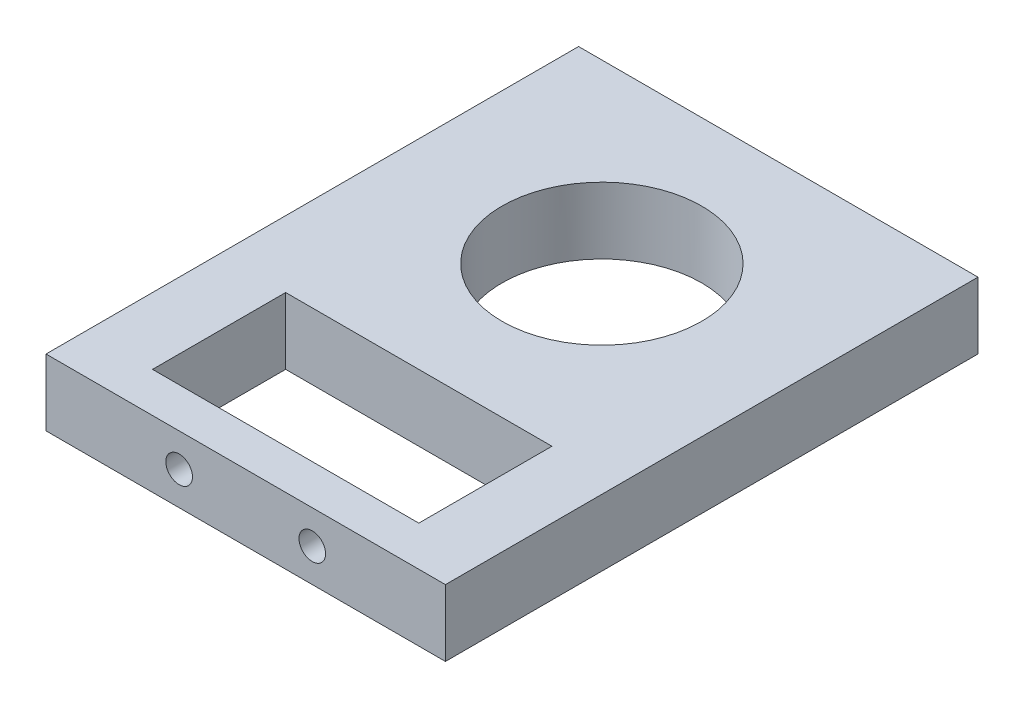
SolidWorks part; units mm, degrees
ref_plane "Front Plane" through (0, 0, 0) normal (0, 0, 1) x (1, 0, 0)
ref_plane "Top Plane" through (0, 0, 0) normal (0, 1, 0) x (1, 0, 0)
ref_plane "Right Plane" through (0, 0, 0) normal (1, 0, 0) x (0, 0, -1)
sketch "Sketch1" plane through (0, 0, 0) normal (0, 1, 0) x (1, 0, 0)
  line L1 (-30, -40) -> (30, -40)
  line L2 (-30, -40) -> (-30, 40)
  line L3 (-30, 40) -> (30, 40)
  line L4 (30, -40) -> (30, 40)
  line L5 (-30, -40) -> (30, 40) construction
  line L6 (-30, 40) -> (30, -40) construction
  point P0 (0, 0)
  dimension "D1" = 80
  dimension "D2" = 60
extrude "Boss-Extrude1" add sketch "Sketch1" along normal blind 10
sketch "Sketch2" plane through (0, 10, 0) normal (0, 1, 0) x (1, 0, 0)
  line L0 (0, -40) -> (0, 13.5) construction
  line L1 (-30, -40) -> (30, -40) construction
  circle A0 centre (0, 13.5) radius 15
  dimension "D2" = 30
  dimension "D1" = 53.5
extrude "Cut-Extrude1" cut sketch "Sketch2" against normal blind 80
sketch "Sketch3" plane through (0, 10, 0) normal (0, 1, 0) x (1, 0, 0)
  line L0 (0, -40) -> (0, -34) construction
  line L1 (-30, -40) -> (30, -40) construction
  line L2 (0, -34) -> (0, -14) construction
  line L5 (20, -34) -> (-20, -34)
  line L6 (20, -34) -> (20, -14)
  line L7 (20, -14) -> (-20, -14)
  line L8 (-20, -34) -> (-20, -14)
  dimension "D1" = 6
  dimension "D2" = 20
  dimension "D3" = 20
  dimension "D4" = 40
extrude "Cut-Extrude2" cut sketch "Sketch3" against normal blind 80
sketch "Sketch4" plane through (0, 0, 34) normal (0, 0, -1) x (-1, 0, 0)
  line L0 (0, 10) -> (0, 0) construction
  line L1 (20, 10) -> (-20, 10) construction
  line L2 (-20, 0) -> (20, 0) construction
  line L3 (20, 5) -> (10, 5) construction
  line L4 (20, 0) -> (20, 10) construction
  circle A0 centre (10, 5) radius 2
  circle A1 centre (-10, 5) radius 2
  dimension "D2" = 4
  dimension "D1" = 10
extrude "Cut-Extrude3" cut sketch "Sketch4" against normal blind 10
